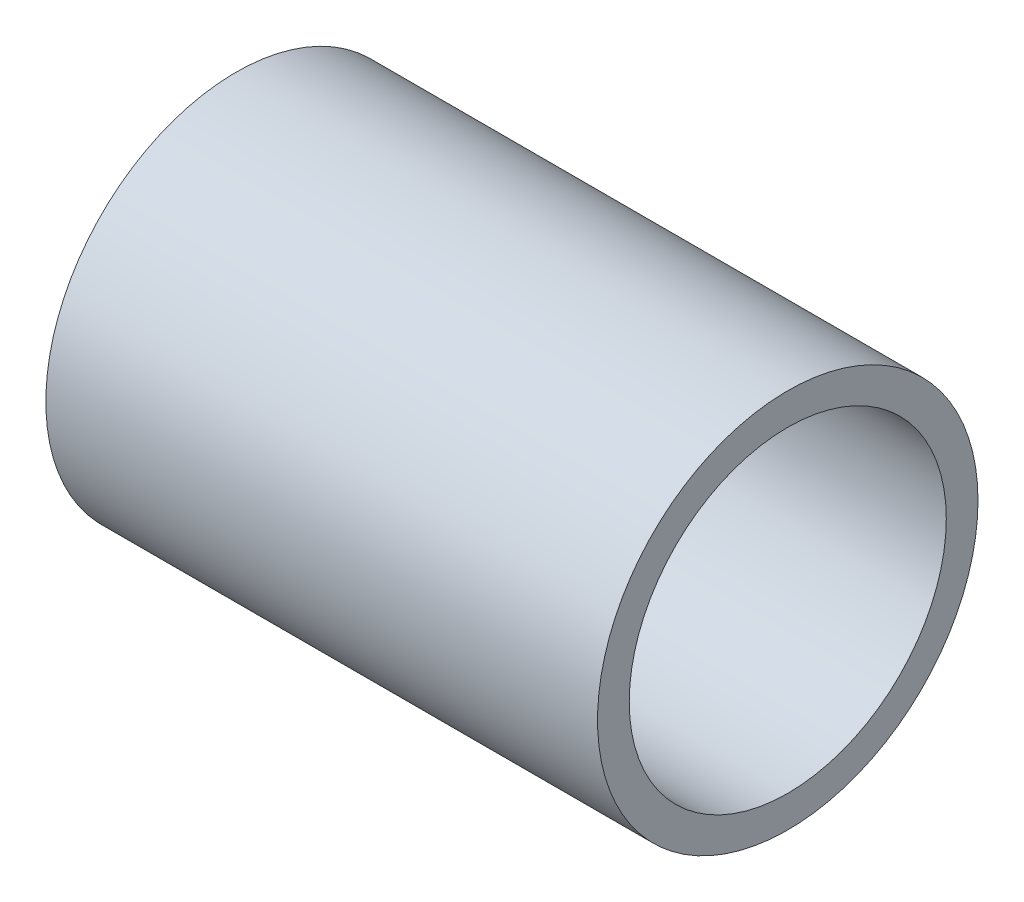
SolidWorks part; units mm, degrees
ref_plane "Front Plane" through (0, 0, 0) normal (0, 0, 1) x (1, 0, 0)
ref_plane "Top Plane" through (0, 0, 0) normal (0, 1, 0) x (1, 0, 0)
ref_plane "Right Plane" through (0, 0, 0) normal (1, 0, 0) x (0, 0, -1)
sketch "Sketch1" plane through (0, 0, 0) normal (1, 0, 0) x (0, 0, -1)
  circle A0 centre (0, 0) radius 5
  circle A1 centre (0, 0) radius 6
  dimension "D1" = 12
  dimension "D2" = 10
extrude "Boss-Extrude1" add sketch "Sketch1" along normal blind 17.4
